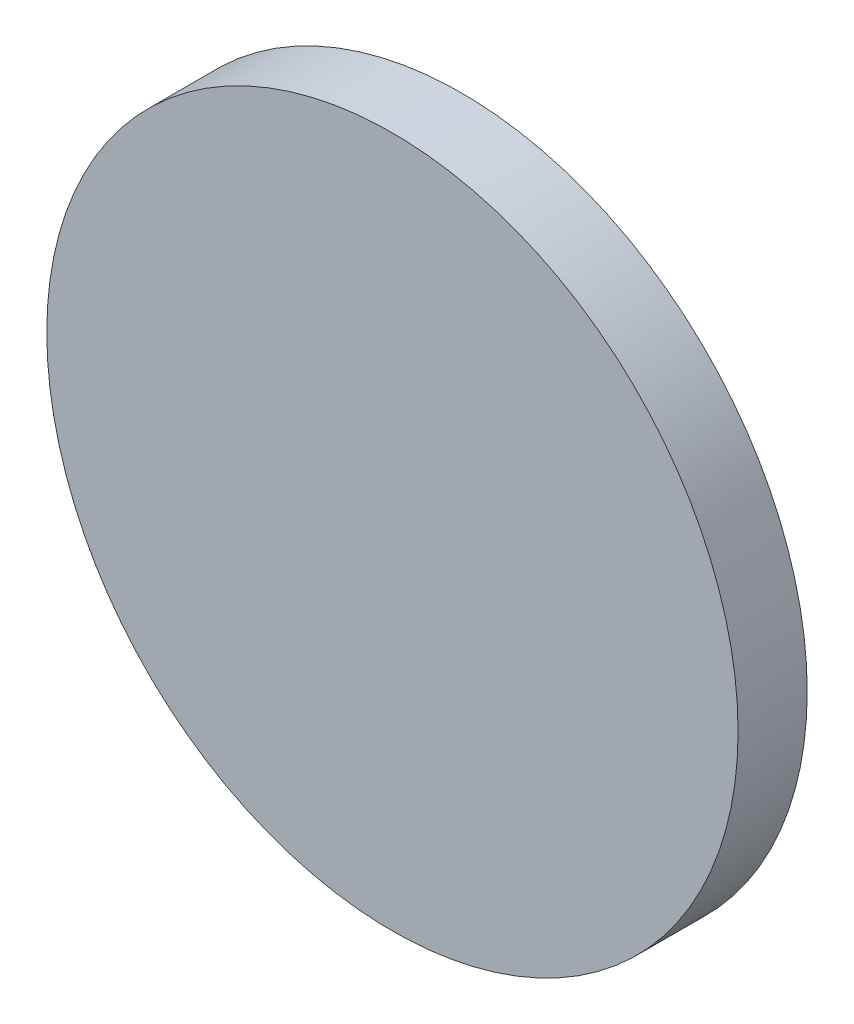
SolidWorks part; units mm, degrees
ref_plane "前视基准面" through (0, 0, 0) normal (0, 0, 1) x (1, 0, 0)
ref_plane "上视基准面" through (0, 0, 0) normal (0, 1, 0) x (1, 0, 0)
ref_plane "右视基准面" through (0, 0, 0) normal (1, 0, 0) x (0, 0, -1)
sketch "草图1" plane through (0, 0, 0) normal (0, 0, 1) x (1, 0, 0)
  circle A0 centre (0, 0) radius 50
  dimension "D1" = 100
extrude "凸台-拉伸1" add sketch "草图1" along normal blind 10
